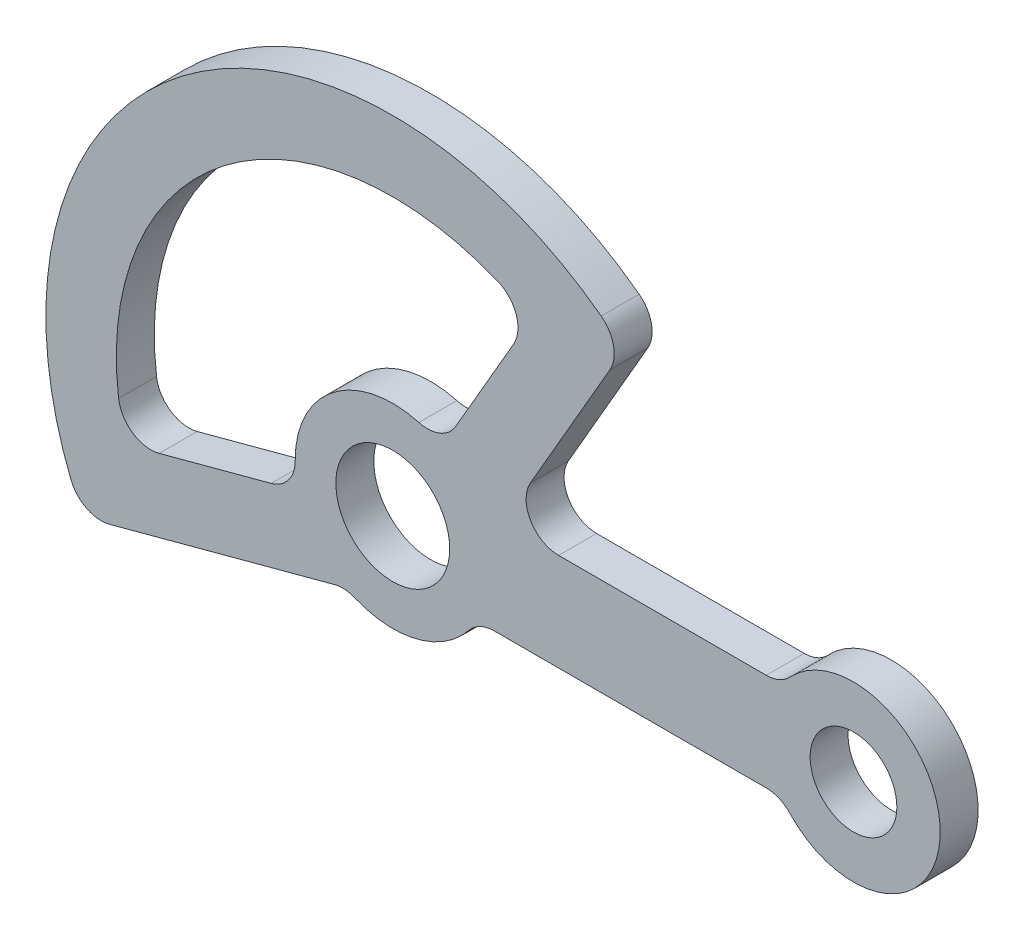
SolidWorks part; units mm, degrees
ref_plane "Front Plane" through (0, 0, 0) normal (0, 0, 1) x (1, 0, 0)
ref_plane "Top Plane" through (0, 0, 0) normal (0, 1, 0) x (1, 0, 0)
ref_plane "Right Plane" through (0, 0, 0) normal (1, 0, 0) x (0, 0, -1)
sketch "Sketch1" plane through (0, 0, 0) normal (0, 0, 1) x (1, 0, 0)
  line L0 (0, 0) -> (5.25, 9.0933)
  line L1 (0, 0) -> (-10.1422, -2.7176)
  line L2 (0, 73.5) -> (0, -25.2518) construction
  line L3 (0, 0) -> (-84.8276, 0) construction
  line L4 (11.619, 20.1246) -> (22.2991, 38.6232)
  line L5 (-22.4461, -6.0144) -> (-43.0786, -11.5429)
  line L6 (-10.7986, -16.3521) -> (-52.2495, -27.4588)
  line L7 (18.735, -9) -> (68.9065, -9)
  line L8 (30.5996, 9) -> (68.9065, 9)
  line L9 (0, 0) -> (111.8533, 0) construction
  line L10 (40.0463, 43.3623) -> (25.4034, 18)
  circle A0 centre (0, 0) radius 10.5
  arc A1 (-6.9343, -16.6107) -> (14.0512, -11.25) centre (0, 0) ccw
  arc A2 (19.3833, 47.1729) -> (-50.5823, -6.5136) centre (0, 0) ccw
  arc A4 (73.2957, -10.9091) -> (73.2957, 10.9091) centre (85, 0) ccw
  circle A5 centre (85, 0) radius 8
  arc A6 (38.4554, 51.1584) -> (-59.3682, -23.9043) centre (0, 0) ccw
  arc A7 (4.8171, 17.3435) -> (-17.9993, -0.1641) centre (0, 0) ccw
  arc A8 (-52.2495, -27.4588) -> (-59.3682, -23.9043) centre (-53.8024, -21.6633) cw
  arc A9 (-10.7986, -16.3521) -> (-6.9343, -16.6107) centre (-9.2457, -22.1476) cw
  arc A10 (18.735, -9) -> (14.0512, -11.25) centre (18.735, -15) ccw
  arc A11 (68.9065, -9) -> (73.2957, -10.9091) centre (68.9065, -15) cw
  arc A12 (68.9065, 9) -> (73.2957, 10.9091) centre (68.9065, 15) ccw
  arc A13 (25.4034, 18) -> (30.5996, 9) centre (30.5996, 15) ccw
  arc A14 (40.0463, 43.3623) -> (38.4554, 51.1584) centre (34.8502, 46.3623) ccw
  arc A15 (22.2991, 38.6232) -> (19.3833, 47.1729) centre (17.103, 41.6232) ccw
  arc A16 (-43.0786, -11.5429) -> (-50.5823, -6.5136) centre (-44.6315, -5.7473) cw
  arc A17 (-22.4461, -6.0144) -> (-17.9993, -0.1641) centre (-23.999, -0.2189) ccw
  arc A18 (11.619, 20.1246) -> (4.8171, 17.3435) centre (6.4228, 23.1246) cw
  point P22 (69.3169, 9)
  point P25 (0, 0)
  point P46 (9, 15.5885)
  dimension "D1" = 21
  dimension "D2" = 36
  dimension "D3" = 102
  dimension "D4" = 6
  dimension "D10" = 32
  dimension "D11" = 16
  dimension "D13" = 64
  dimension "D5" = 30
  dimension "D6" = 15
  dimension "D7" = 13
  dimension "D8" = 13
  dimension "D9" = 18
  dimension "D12" = 85
extrude "Boss-Extrude1" add sketch "Sketch1" along normal blind 7 contours L10 A14 A6 A8 L6 A9 A1 A10 L7 A11 A4 A12 L8 A13 A0 A5 L4 A18 A7 A17 L5 A16 A2 A15
